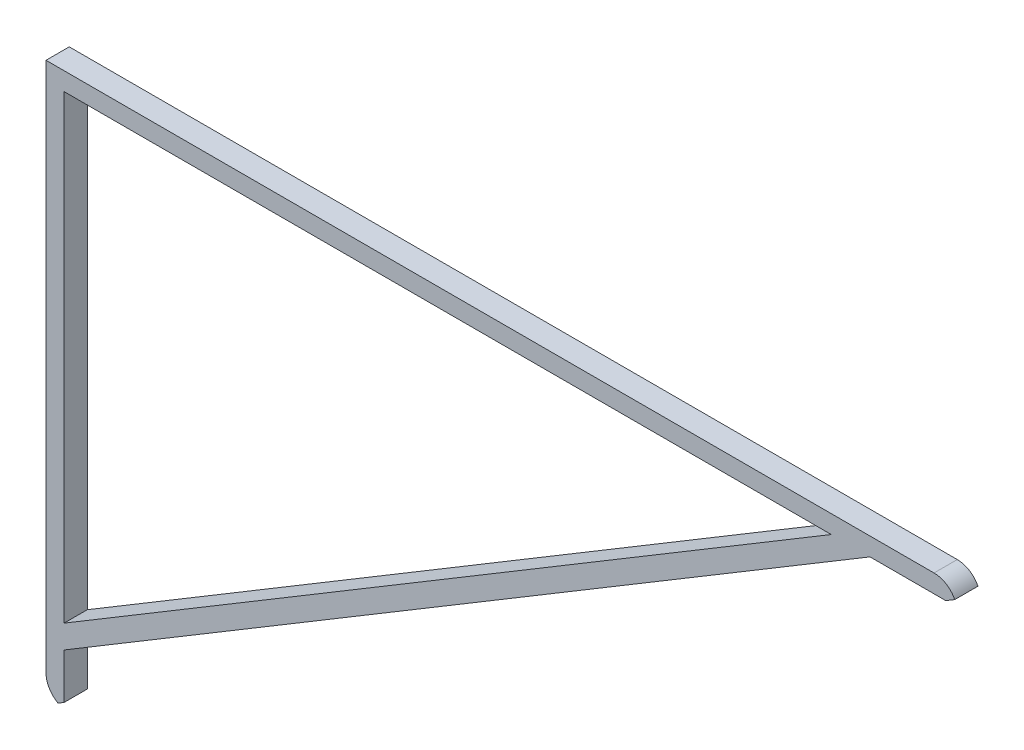
SolidWorks part; units mm, degrees
material "Alliage 1060"
ref_plane "Plan de face" through (0, 0, 0) normal (0, 0, 1) x (1, 0, 0)
ref_plane "Plan de dessus" through (0, 0, 0) normal (0, 1, 0) x (1, 0, 0)
ref_plane "Plan de droite" through (0, 0, 0) normal (1, 0, 0) x (0, 0, -1)
sketch "Esquisse1" plane through (0, 0, 0) normal (0, 0, 1) x (1, 0, 0)
  line L0 (0, 0) -> (190.9852, 0)
  line L2 (0, -114.0659) -> (0, 0)
  line L5 (0, 0) -> (0, -120) construction
  line L6 (0, -120) -> (2.5893, -118.4464) construction
  line L7 (200, 0) -> (0, 0) construction
  line L8 (3.8891, -107.8891) -> (177.2224, -3.8891)
  line L9 (195.4425, -2.7345) -> (200, 0) construction
  line L10 (195.4425, -2.7345) -> (193.5182, -3.8891)
  line L14 (3.8891, -102.8891) -> (168.8891, -3.8891)
  line L15 (0, 0) -> (3.8891, -3.8891) construction
  line L16 (3.8891, -3.8891) -> (3.8891, -102.8891)
  line L17 (3.8891, -3.8891) -> (168.8891, -3.8891)
  line L18 (3.8891, -117.6665) -> (2.5893, -118.4464)
  line L19 (177.2224, -3.8891) -> (193.5182, -3.8891)
  line L20 (3.8891, -107.8891) -> (3.8891, -117.6665)
  arc A0 (190.9852, 0) -> (195.4425, -2.7345) centre (190.9852, -5) cw
  arc A1 (2.5893, -118.4464) -> (0, -114.0659) centre (5, -114.0659) cw
  point P6 (200, 0)
  point P9 (0, -120)
  point P10 (0, 0)
  point P20 (195.9231, -3.5355)
  point P21 (2.5893, -118.4464)
  dimension "D3" = 5
  dimension "D4" = 5
  dimension "D5" = 165
  dimension "D1" = 200
  dimension "D2" = 120
  dimension "D6" = 5
  dimension "D7" = 5.5
extrude "Boss.-Extru.4" add sketch "Esquisse1" along normal blind 5
